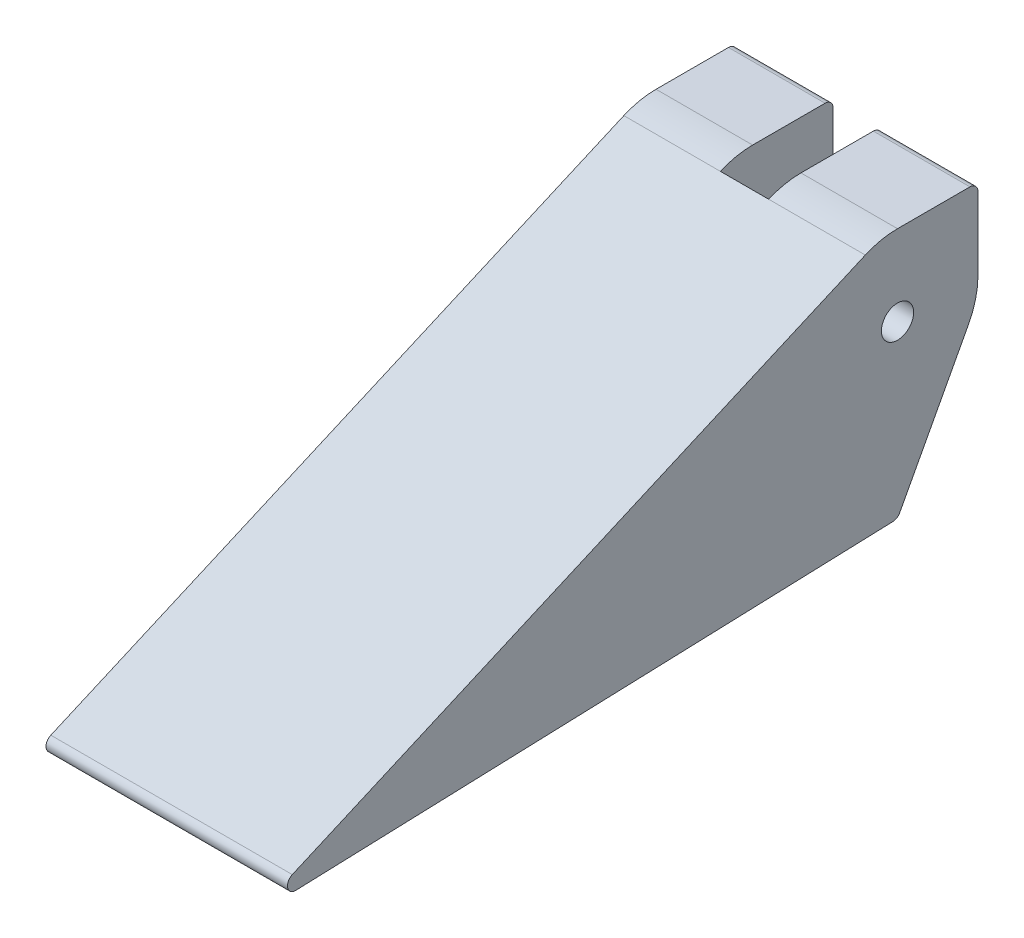
SolidWorks part; units mm, degrees
ref_plane "Front Plane" through (0, 0, 0) normal (0, 0, 1) x (1, 0, 0)
ref_plane "Top Plane" through (0, 0, 0) normal (0, 1, 0) x (1, 0, 0)
ref_plane "Right Plane" through (0, 0, 0) normal (1, 0, 0) x (0, 0, -1)
sketch "Sketch1" plane through (0, 0, 0) normal (1, 0, 0) x (0, 0, -1)
  line L4 (11.1993, -5.9888) -> (0.3448, -26.2872)
  line L5 (0, 0) -> (0, 2.54) construction
  line L6 (-0.7308, -26.9576) -> (-94.9388, -30.2474)
  line L7 (-5.0795, 11.64) -> (-95.4911, -27.8142)
  line L8 (12.7, 0) -> (12.7, 11.43)
  line L9 (11.43, 12.7) -> (0, 12.7)
  line L10 (0, 12.7) -> (0, 17.319) construction
  circle A0 centre (0, 0) radius 2.54
  arc A1 (0, 12.7) -> (-5.0795, 11.64) centre (0, 0) ccw
  arc A2 (11.1993, -5.9888) -> (12.7, 0) centre (0, 0) ccw
  arc A3 (0.3448, -26.2872) -> (-0.7308, -26.9576) centre (-0.7751, -25.6883) cw
  arc A4 (12.7, 11.43) -> (11.43, 12.7) centre (11.43, 11.43) ccw
  arc A5 (-94.9388, -30.2474) -> (-95.4911, -27.8142) centre (-94.9831, -28.9782) cw
  point P14 (0, -26.932)
  point P19 (-101.6, -30.48)
  dimension "D1" = 5.08
  dimension "D2" = 10.16
  dimension "D5" = 1.27
  dimension "D3" = 88
  dimension "D4" = 30.48
  dimension "D6" = 101.6
extrude "Boss-Extrude1" add sketch "Sketch1" along normal blind 38.1
ref_plane "Plane1" through (19.05, 0, 0) normal (1, 0, 0) x (0, 0, -1)
sketch "Sketch4" plane through (19.05, 0, 0) normal (1, 0, 0) x (0, 0, -1)
  line L0 (-5.08, 0) -> (-5.08, 25.7922)
  line L1 (-5.08, 25.7922) -> (14.1721, 25.7922)
  line L2 (14.1721, 25.7922) -> (14.1721, -34.7067)
  line L3 (14.1721, -34.7067) -> (-4.3994, -2.54)
  circle A0 centre (0, 0) radius 5.08
  point P5 (14.0551, -34.7543)
  dimension "D1" = 10.16
  dimension "D2" = 30
extrude "Cut-Extrude1" cut sketch "Sketch4" against normal blind 3.81 and the other way blind 3.81 contours A0 L3 L2 L1 L0 | A0
